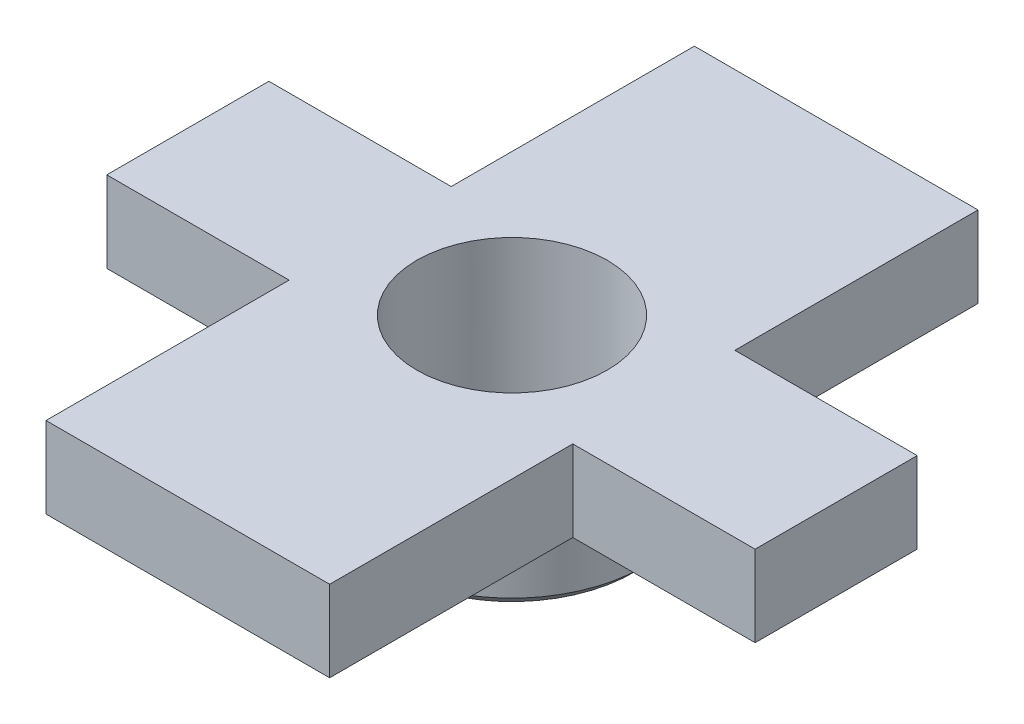
SolidWorks part; units mm, degrees
ref_plane "Ebene vorne" through (0, 0, 0) normal (0, 0, 1) x (1, 0, 0)
ref_plane "Ebene oben" through (0, 0, 0) normal (0, 1, 0) x (1, 0, 0)
ref_plane "Ebene rechts" through (0, 0, 0) normal (1, 0, 0) x (0, 0, -1)
sketch "Skizze4" plane through (0, 0, 0) normal (0, 1, 0) x (1, 0, 0)
  line L0 (-49.0844, 0) -> (52.7488, 0) construction
  line L1 (-55, 0) -> (55, 0) construction
  line L2 (0, 36.0148) -> (0, -34.5812) construction
  line L3 (0, -55) -> (0, 55) construction
  line L4 (-8, -2) -> (-8, 2)
  line L5 (-8, 2) -> (-3.5, 2)
  line L6 (-3.5, 2) -> (-3.5, 8)
  line L7 (-3.5, 8) -> (3.5, 8)
  line L8 (-3.5, -8) -> (3.5, -8)
  line L9 (-3.5, -2) -> (-3.5, -8)
  line L10 (-8, -2) -> (-3.5, -2)
  line L11 (8, -2) -> (3.5, -2)
  line L12 (3.5, -2) -> (3.5, -8)
  line L13 (3.5, 2) -> (3.5, 8)
  line L14 (8, 2) -> (3.5, 2)
  line L15 (8, -2) -> (8, 2)
  point P18 (-8, 0)
  point P21 (0, -8)
  point P22 (0, 8)
  point P24 (8, 0)
  dimension "D1" = 2
  dimension "D2" = 3.5
  dimension "D3" = 4.5
  dimension "D4" = 6
extrude "Grundplatte Kreuz " add sketch "Skizze4" along normal blind 2
sketch "Skizze11" plane through (0, 0, 0) normal (0, 1, 0) x (1, 0, 0)
  line L0 (5.8896, 0) -> (-5.2924, 0) construction
  line L1 (-1.1, 0) -> (1.1, 0) construction
  circle A0 centre (0, 0) radius 1.25
  dimension "D1" = 2.5
extrude "Mittelbohrung" cut sketch "Skizze11" along normal through all both and the other way through all
sketch "Skizze12" plane through (0, 0, 0) normal (0, -1, 0) x (1, 0, 0)
  line L0 (4.3451, 0) -> (-4.5305, 0) construction
  line L1 (1.1, 0) -> (-1.1, 0) construction
  circle A0 centre (0, 0) radius 3.25
  dimension "D1" = 6.5
extrude "Aufsatz-Linear austragen2" add sketch "Skizze12" along normal blind 2
chamfer "Fase1" distance 0.25 angle 45 1 edges at (0, -2, -3.25)
sketch "Skizze13" plane through (0, -2, 0) normal (0, -1, 0) x (1, 0, 0)
  circle A0 centre (0, 0) radius 2.35
  dimension "D1" = 4.7
extrude "Schnitt-Linear austragen1" cut sketch "Skizze13" against normal up to surface (4 mm away) up to face at (0, 2, 1.25)
